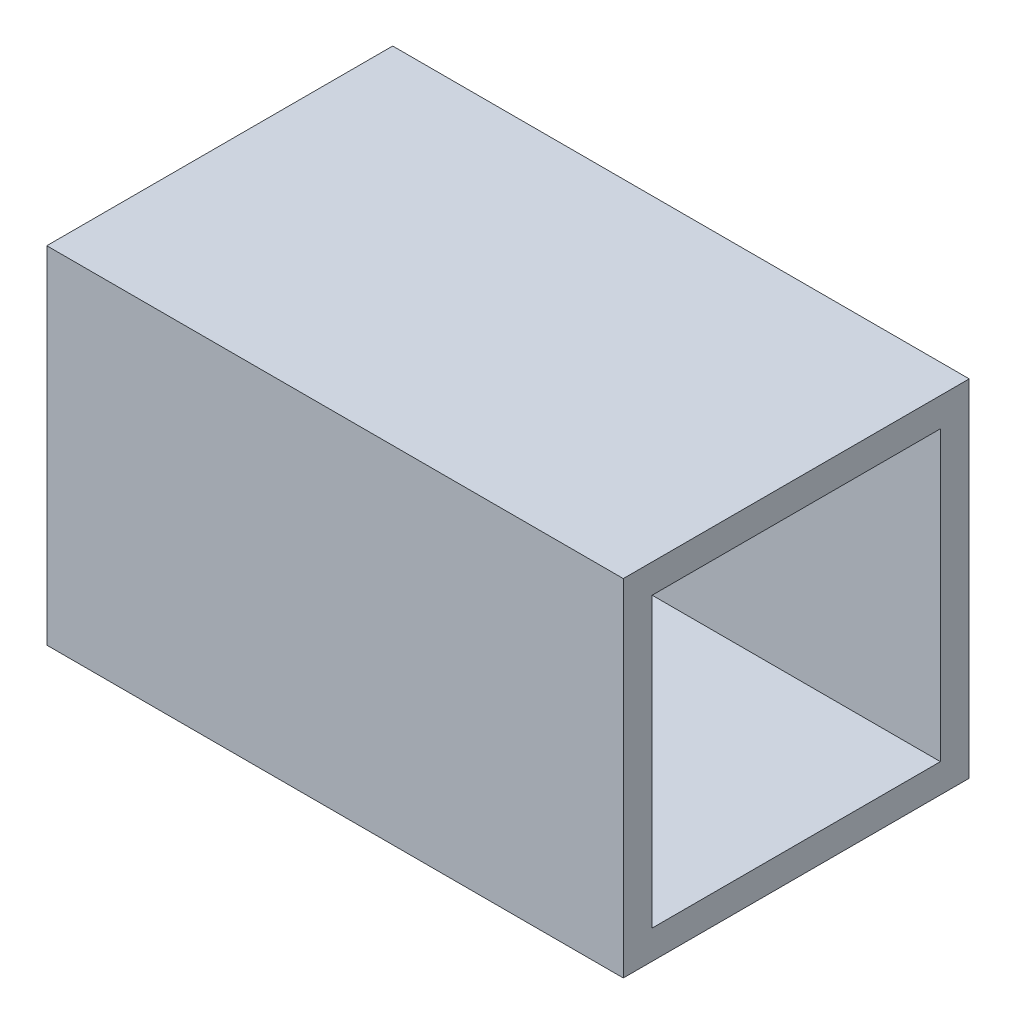
SolidWorks part; units mm, degrees
ref_plane "Front Plane" through (0, 0, 0) normal (0, 0, 1) x (1, 0, 0)
ref_plane "Top Plane" through (0, 0, 0) normal (0, 1, 0) x (1, 0, 0)
ref_plane "Right Plane" through (0, 0, 0) normal (1, 0, 0) x (0, 0, -1)
sketch "Sketch1" plane through (0, 0, 0) normal (1, 0, 0) x (0, 0, -1)
  line L0 (-12, 12) -> (12, 12)
  line L1 (-10, 10) -> (10, 10)
  line L2 (-10, 10) -> (-10, -10)
  line L3 (-10, -10) -> (10, -10)
  line L4 (10, 10) -> (10, -10)
  line L5 (-10, 10) -> (10, -10) construction
  line L6 (-10, -10) -> (10, 10) construction
  line L7 (12, 12) -> (12, -12)
  line L8 (-12, -12) -> (12, -12)
  line L9 (-12, 12) -> (-12, -12)
  point P0 (0, 0)
  dimension "D2" = 20
  dimension "D3" = 20
  dimension "D1" = 2
extrude "Boss-Extrude1" add sketch "Sketch1" along normal blind 40
sketch "Sketch2" plane through (0, 0, -12) normal (0, 0, -1) x (-1, 0, 0)
  line L0 (0, -12) -> (0, 12) construction
  circle A0 centre (-20, 0) radius 5
  dimension "D1" = 20
extrude "Boss-Extrude2" add sketch "Sketch2" along normal blind 7
